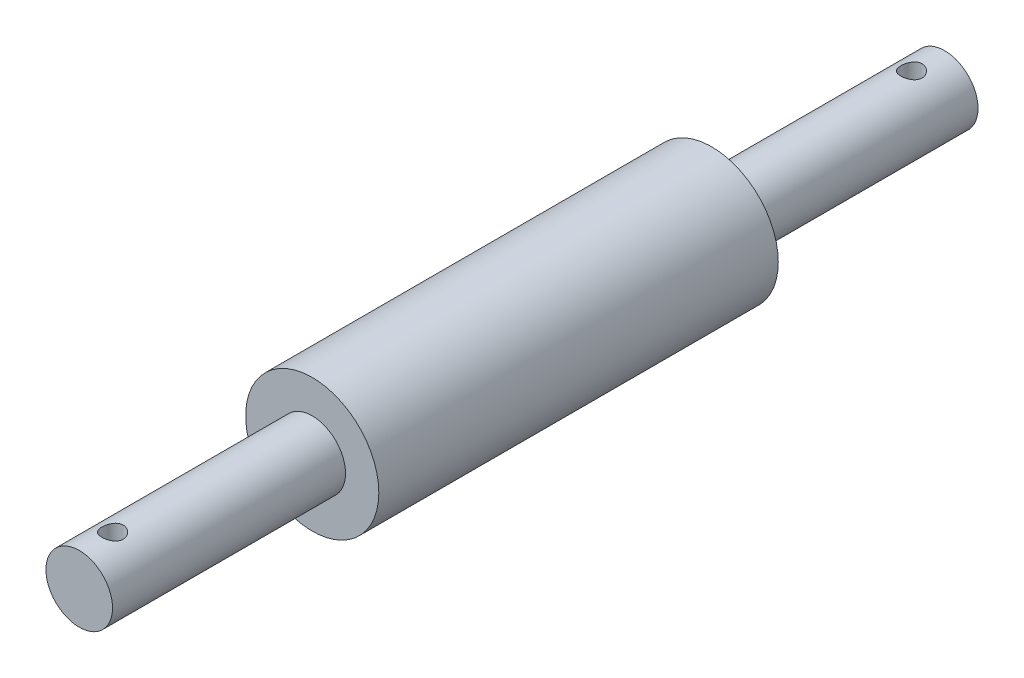
SolidWorks part; units mm, degrees
ref_plane "前视基准面" through (0, 0, 0) normal (0, 0, 1) x (1, 0, 0)
ref_plane "上视基准面" through (0, 0, 0) normal (0, 1, 0) x (1, 0, 0)
ref_plane "右视基准面" through (0, 0, 0) normal (1, 0, 0) x (0, 0, -1)
other "Configuration Table"
sketch "草图1" plane through (0, 0, 0) normal (0, 0, 1) x (1, 0, 0)
  circle A0 centre (0, 0) radius 5
  dimension "D1" = 10
extrude "凸台-拉伸1" add sketch "草图1" along normal blind 130
sketch "草图2" plane through (0, 0, 130) normal (0, 0, 1) x (1, 0, 0)
  circle A0 centre (0, 0) radius 10
  dimension "D1" = 20
extrude "凸台-拉伸2" add sketch "草图2" against normal offset from surface (60 mm away) 35 from offset 35 up to face at (5, 0, 0) offset against normal yes
sketch "草图3" plane through (0, 0, 0) normal (0, 1, 0) x (1, 0, 0)
  line L0 (5, 0) -> (-5, 0) construction
  line L1 (-5, -130) -> (5, -130) construction
  circle A0 centre (0, -5) radius 1.6
  circle A1 centre (0, -125) radius 1.6
  point P9 (0, 0)
  dimension "D2" = 3.2
  dimension "D3" = 3.2
  dimension "D1" = 5
  dimension "D4" = 5
extrude "切除-拉伸1" cut sketch "草图3" against normal through all both and the other way through all contours A1 | A0
